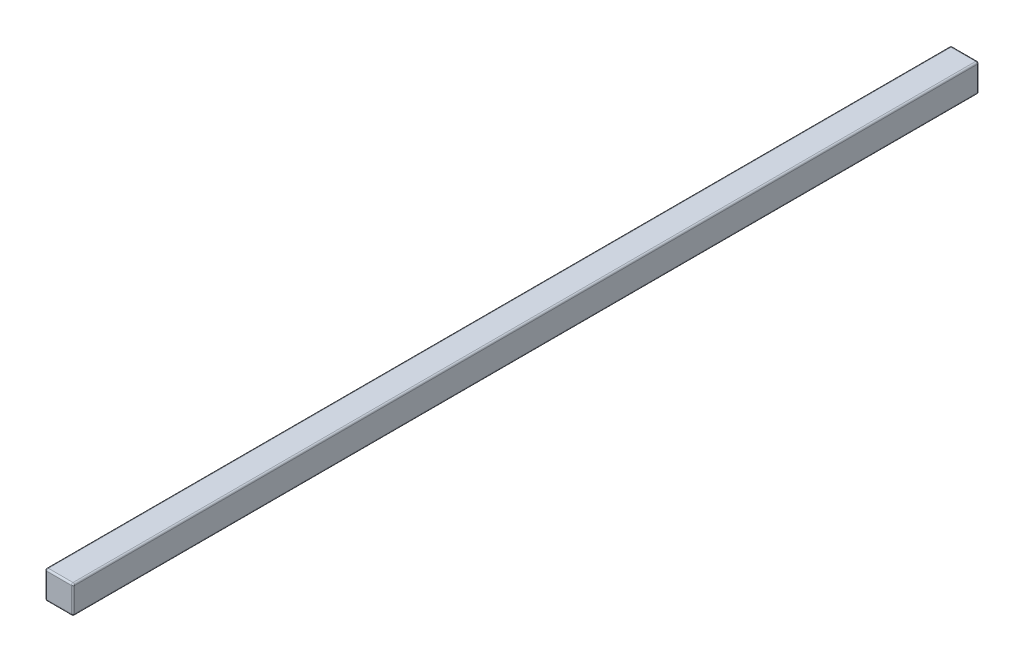
SolidWorks part; units mm, degrees
ref_plane "Front Plane" through (0, 0, 0) normal (0, 0, 1) x (1, 0, 0)
ref_plane "Top Plane" through (0, 0, 0) normal (0, 1, 0) x (1, 0, 0)
ref_plane "Right Plane" through (0, 0, 0) normal (1, 0, 0) x (0, 0, -1)
sketch "Sketch1" plane through (0, 0, 0) normal (0, 0, 1) x (1, 0, 0)
  line L1 (-12.5, -12.5) -> (12.5, -12.5)
  line L2 (-12.5, -12.5) -> (-12.5, 12.5)
  line L3 (-12.5, 12.5) -> (12.5, 12.5)
  line L4 (12.5, -12.5) -> (12.5, 12.5)
  line L5 (-12.5, -12.5) -> (12.5, 12.5) construction
  line L6 (-12.5, 12.5) -> (12.5, -12.5) construction
  point P0 (0, 0)
  dimension "D1" = 25
  dimension "D2" = 25
extrude "Boss-Extrude1" add sketch "Sketch1" along normal blind 808.79
fillet "Fillet1" radius 1.5 12 edges at (0, -12.5, 808.79) (0, -12.5, 0) (-12.5, 0, 808.79) (-12.5, -12.5, 404.395) (-12.5, 0, 0) (12.5, -12.5, 404.395) (12.5, 0, 808.79) (12.5, 0, 0) (12.5, 12.5, 404.395) (0, 12.5, 808.79) (-12.5, 12.5, 404.395) (0, 12.5, 0)
